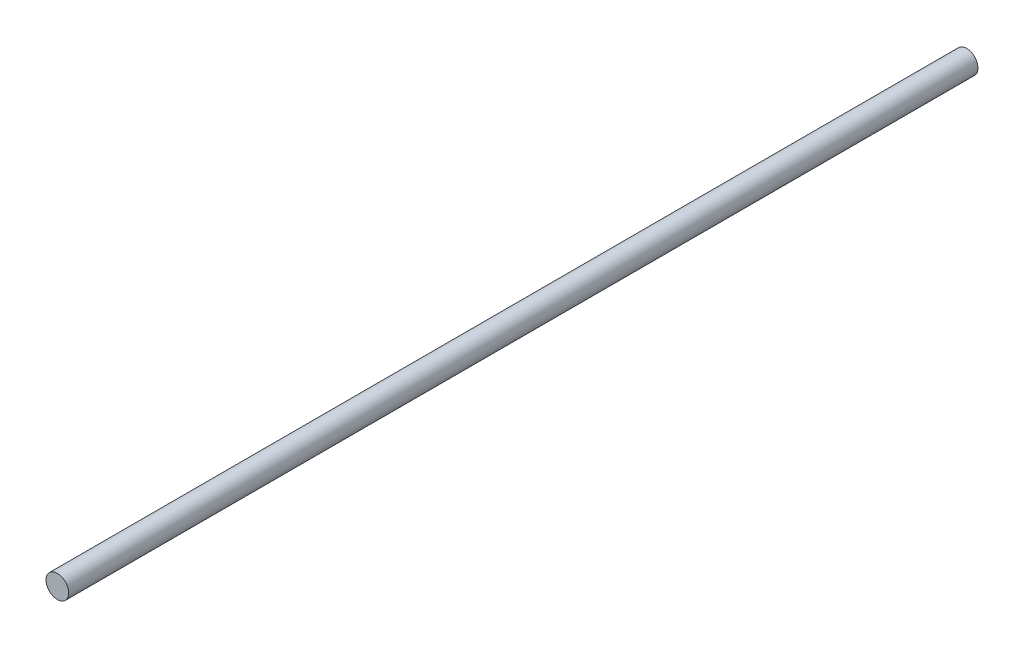
SolidWorks part; units mm, degrees
ref_plane "前基準面" through (0, 0, 0) normal (0, 0, 1) x (1, 0, 0)
ref_plane "上基準面" through (0, 0, 0) normal (0, 1, 0) x (1, 0, 0)
ref_plane "右基準面" through (0, 0, 0) normal (1, 0, 0) x (0, 0, -1)
sketch "草圖1" plane through (0, 0, 0) normal (0, 0, 1) x (1, 0, 0)
  circle A0 centre (0, 0) radius 5
  dimension "D1" = 10
extrude "填料-伸長1" add sketch "草圖1" along normal blind 400
